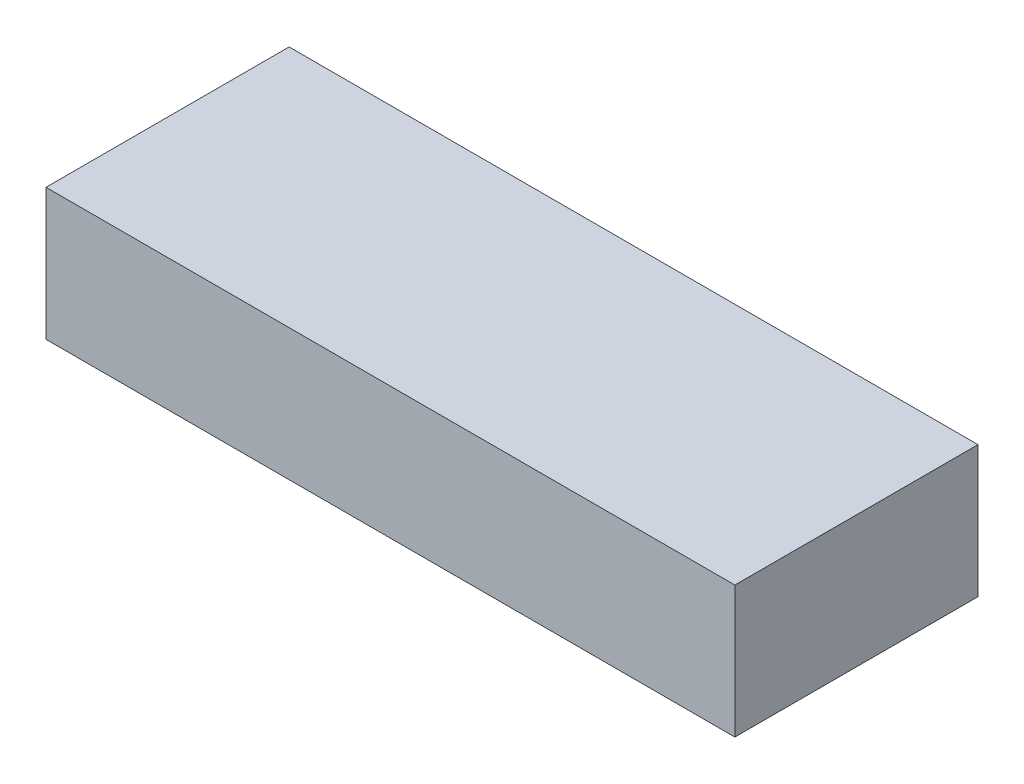
SolidWorks part; units mm, degrees
ref_plane "Front Plane" through (0, 0, 0) normal (0, 0, 1) x (1, 0, 0)
ref_plane "Top Plane" through (0, 0, 0) normal (0, 1, 0) x (1, 0, 0)
ref_plane "Right Plane" through (0, 0, 0) normal (1, 0, 0) x (0, 0, -1)
sketch "Sketch1" plane through (0, 0, 0) normal (1, 0, 0) x (0, 0, -1)
  line L1 (0, 0) -> (30.48, 0)
  line L2 (0, 0) -> (0, 16.51)
  line L3 (0, 16.51) -> (30.48, 16.51)
  line L4 (30.48, 0) -> (30.48, 16.51)
  dimension "D1" = 30.48
  dimension "D2" = 16.51
extrude "Boss-Extrude1" add sketch "Sketch1" along normal blind 86.36
